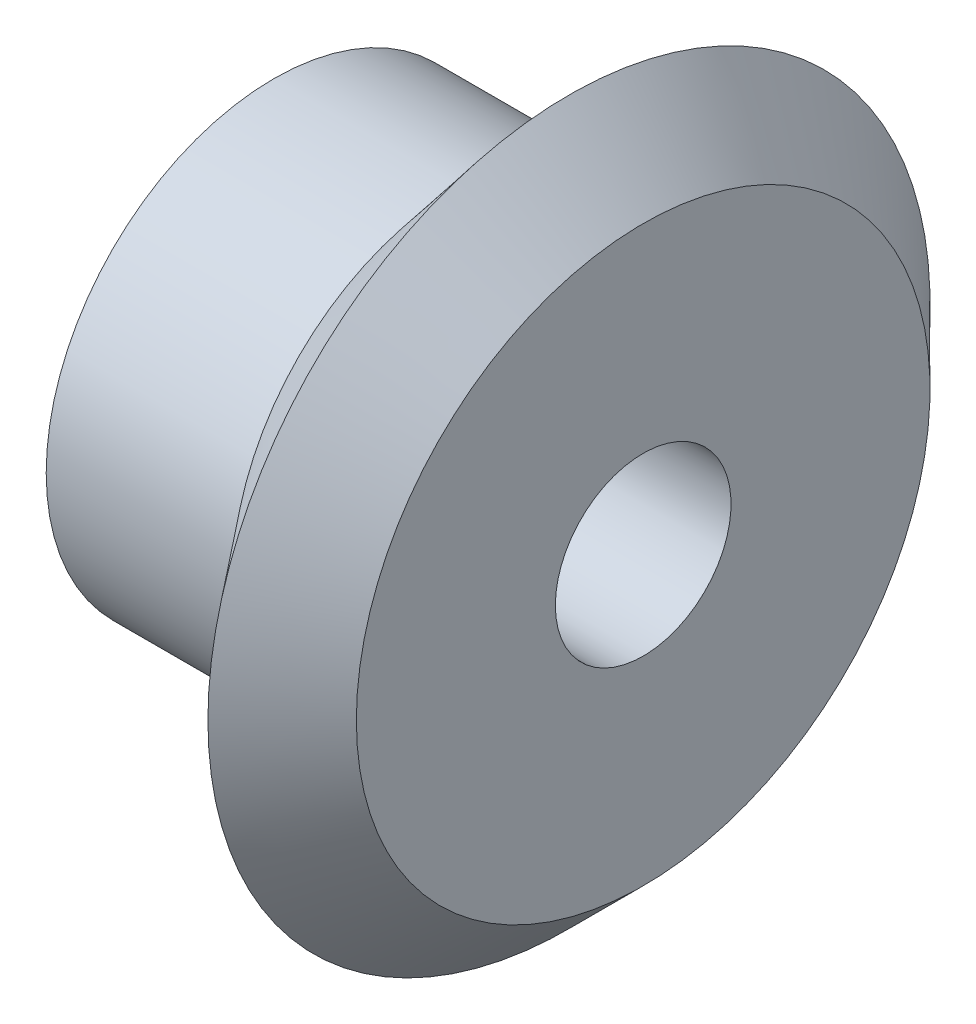
SolidWorks part; units mm, degrees
ref_plane "Front Plane" through (0, 0, 0) normal (0, 0, 1) x (1, 0, 0)
ref_plane "Top Plane" through (0, 0, 0) normal (0, 1, 0) x (1, 0, 0)
ref_plane "Right Plane" through (0, 0, 0) normal (1, 0, 0) x (0, 0, -1)
sketch "Sketch1" plane through (0, 0, 0) normal (0, 0, 1) x (1, 0, 0)
  line L0 (4.8433, 8) -> (2.7733, 10.07)
  line L1 (-5.4567, 6.35) -> (-0.2667, 6.35)
  line L2 (-5.4567, 2.45) -> (-5.4567, 6.35)
  line L3 (-22.2616, 0) -> (68.45, 0) construction
  line L4 (4.8433, 2.45) -> (4.8433, 8)
  line L5 (2.7733, 10.07) -> (-0.2667, 6.35)
  line L6 (-5.4567, 2.45) -> (4.8433, 2.45)
  dimension "D1" = 2.45
  dimension "D2" = 8
  dimension "D3" = 10.07
  dimension "D4" = 10.3
  dimension "D5" = 5.11
  dimension "D6" = 6.35
  dimension "D7" = 135
revolve "Revolve1" add sketch "Sketch1" angle 360 about L3
